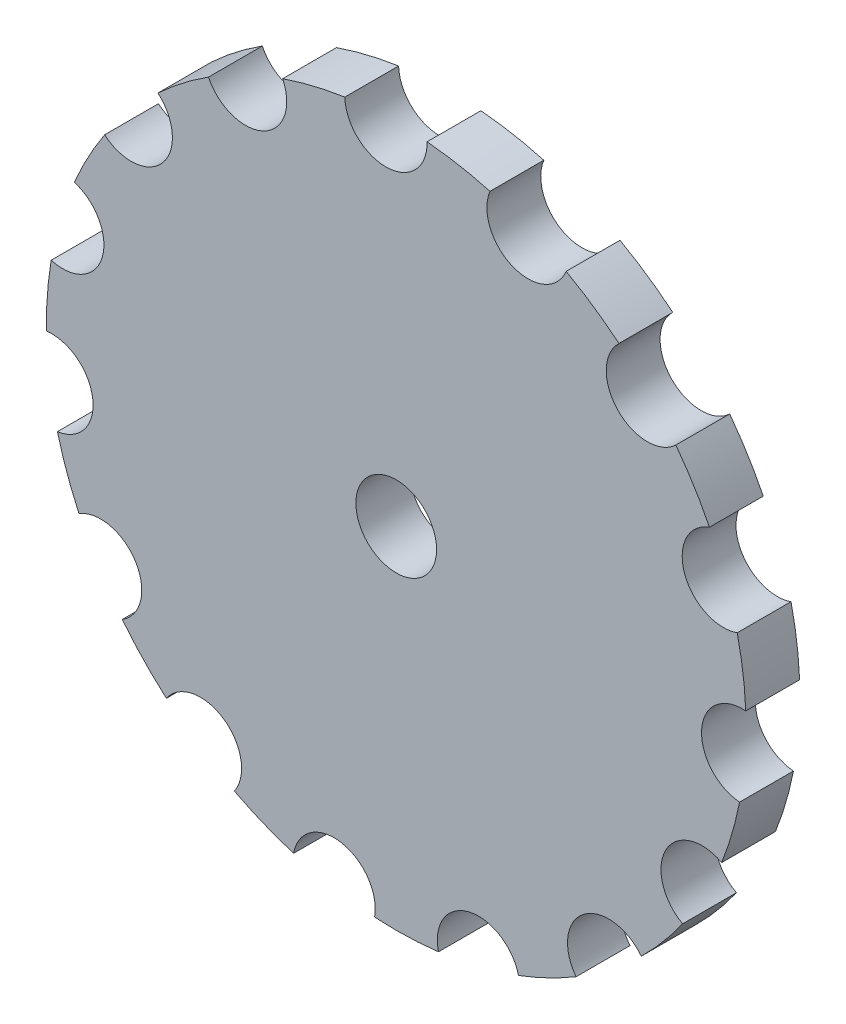
SolidWorks part; units mm, degrees
ref_plane "Front Plane" through (0, 0, 0) normal (0, 0, 1) x (1, 0, 0)
ref_plane "Top Plane" through (0, 0, 0) normal (0, 1, 0) x (1, 0, 0)
ref_plane "Right Plane" through (0, 0, 0) normal (1, 0, 0) x (0, 0, -1)
sketch "Sketch1" plane through (0, 0, 0) normal (0, 0, 1) x (1, 0, 0)
  circle A0 centre (0, 0) radius 65
  dimension "D1" = 130
extrude "Boss-Extrude1" add sketch "Sketch1" along normal blind 10
sketch "Sketch2" plane through (0, 0, 0) normal (0, 0, -1) x (-1, 0, 0)
  arc A0 (-5.7309, 64.7469) -> (-17.4189, 62.6225) centre (0, 0) ccw
  arc A1 (21.0995, 61.4802) -> (9.558, 64.2934) centre (0, 0) ccw
  arc A2 (44.2816, 47.583) -> (34.8821, 54.8474) centre (0, 0) ccw
  arc A3 (59.807, 25.4582) -> (54.1749, 35.9178) centre (0, 0) ccw
  arc A4 (64.9912, -1.0684) -> (64.1003, 10.7776) centre (0, 0) ccw
  arc A5 (58.9379, -27.4104) -> (62.9421, -16.2261) centre (0, 0) ccw
  arc A6 (42.6936, -49.0128) -> (50.9008, -40.4241) centre (0, 0) ccw
  arc A7 (19.0672, -62.1405) -> (30.0582, -57.6325) centre (0, 0) ccw
  arc A8 (-7.856, -64.5235) -> (4.0183, -64.8757) centre (0, 0) ccw
  arc A9 (-33.4209, -55.7498) -> (-22.7164, -60.9013) centre (0, 0) ccw
  arc A10 (-53.207, -37.3365) -> (-45.5233, -46.3965) centre (0, 0) ccw
  arc A11 (-63.7931, -12.4673) -> (-60.4587, -23.8693) centre (0, 0) ccw
  arc A12 (-63.3489, 14.5575) -> (-64.9403, 2.7851) centre (0, 0) ccw
  arc A13 (-51.951, 39.0653) -> (-58.1931, 28.9579) centre (0, 0) ccw
  arc A14 (-31.5703, 56.8183) -> (-41.3838, 50.1236) centre (0, 0) ccw
  circle A16 centre (0, 0) radius 65 construction
  arc A18 (-31.5703, 56.8183) -> (-17.4189, 62.6225) centre (-24.4946, 59.7204) ccw
  arc A19 (-5.7309, 64.7469) -> (9.558, 64.2934) centre (1.9136, 64.5202) ccw
  arc A20 (21.0995, 61.4802) -> (34.8821, 54.8474) centre (27.9908, 58.1638) ccw
  arc A21 (44.2816, 47.583) -> (54.1749, 35.9178) centre (49.2282, 41.7504) ccw
  arc A22 (59.807, 25.4582) -> (64.1003, 10.7776) centre (61.9536, 18.1179) ccw
  arc A23 (64.9912, -1.0684) -> (62.9421, -16.2261) centre (63.9667, -8.6473) ccw
  arc A24 (58.9379, -27.4104) -> (50.9008, -40.4241) centre (54.9193, -33.9173) ccw
  arc A25 (42.6936, -49.0128) -> (30.0582, -57.6325) centre (36.3759, -53.3227) ccw
  arc A26 (19.0672, -62.1405) -> (4.0183, -64.8757) centre (11.5428, -63.5081) ccw
  arc A27 (-7.856, -64.5235) -> (-22.7164, -60.9013) centre (-15.2862, -62.7124) ccw
  arc A28 (-33.4209, -55.7498) -> (-45.5233, -46.3965) centre (-39.4721, -51.0731) ccw
  arc A29 (-53.207, -37.3365) -> (-60.4587, -23.8693) centre (-56.8329, -30.6029) ccw
  arc A30 (-63.7931, -12.4673) -> (-64.9403, 2.7851) centre (-64.3667, -4.8411) ccw
  arc A31 (-63.3489, 14.5575) -> (-58.1931, 28.9579) centre (-60.771, 21.7577) ccw
  arc A32 (-51.951, 39.0653) -> (-41.3838, 50.1236) centre (-46.6674, 44.5945) ccw
  point P34 (0, 0)
  point P80 (0, 0)
  dimension "D1" = 15
  dimension "D2" = 15
extrude "Cut-Extrude4" cut sketch "Sketch2" against normal through all both and the other way through all flip side to cut
sketch "Sketch3" plane through (0, 0, 10) normal (0, 0, 1) x (1, 0, 0)
  circle A0 centre (0, 0) radius 7.5
  dimension "D1" = 15
extrude "Cut-Extrude5" cut sketch "Sketch3" against normal blind 10
